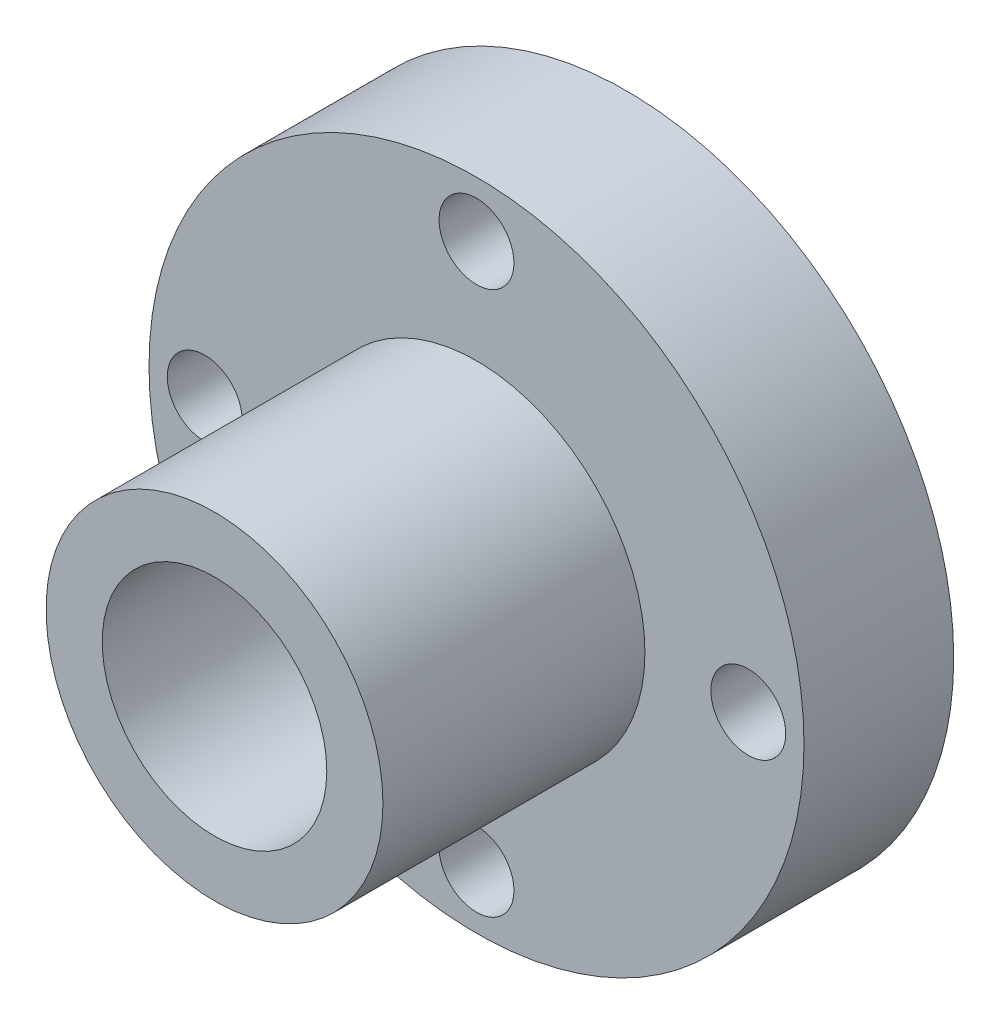
SolidWorks part; units mm, degrees
ref_plane "Plano frontal" through (0, 0, 0) normal (0, 0, 1) x (1, 0, 0)
ref_plane "Plano superior" through (0, 0, 0) normal (0, 1, 0) x (1, 0, 0)
ref_plane "Plano direito" through (0, 0, 0) normal (1, 0, 0) x (0, 0, -1)
sketch "Esboço2" plane through (0, 0, 0) normal (0, 0, 1) x (1, 0, 0)
  circle A2 centre (0, 0) radius 17.5
  dimension "D1" = 35
extrude "Ressalto-extrusão2" add sketch "Esboço2" along normal blind 8
sketch "Esboço6" plane through (0, 0, 8) normal (0, 0, 1) x (1, 0, 0)
  circle A0 centre (0, 14.5232) radius 2
  circle A5 centre (14.5232, 0) radius 2
  circle A6 centre (0, -14.5232) radius 2
  circle A7 centre (-14.5232, 0) radius 2
  point P11 (0, 0)
  point P12 (0, 0)
  dimension "D1" = 4
  dimension "D2" = 4
extrude "Corte-extrusão2" cut sketch "Esboço6" against normal through all both and the other way through all
sketch "Esboço7" plane through (0, 0, 8) normal (0, 0, 1) x (1, 0, 0)
  circle A0 centre (0, 0) radius 9
  circle A1 centre (0, 0) radius 6
  dimension "D1" = 18
  dimension "D2" = 12
extrude "Ressalto-extrusão3" add sketch "Esboço7" along normal blind 14
sketch "Esboço8" plane through (0, 0, 8) normal (0, 0, 1) x (1, 0, 0)
  circle A0 centre (0, 0) radius 6
extrude "Corte-extrusão3" cut sketch "Esboço8" against normal through all both and the other way through all
